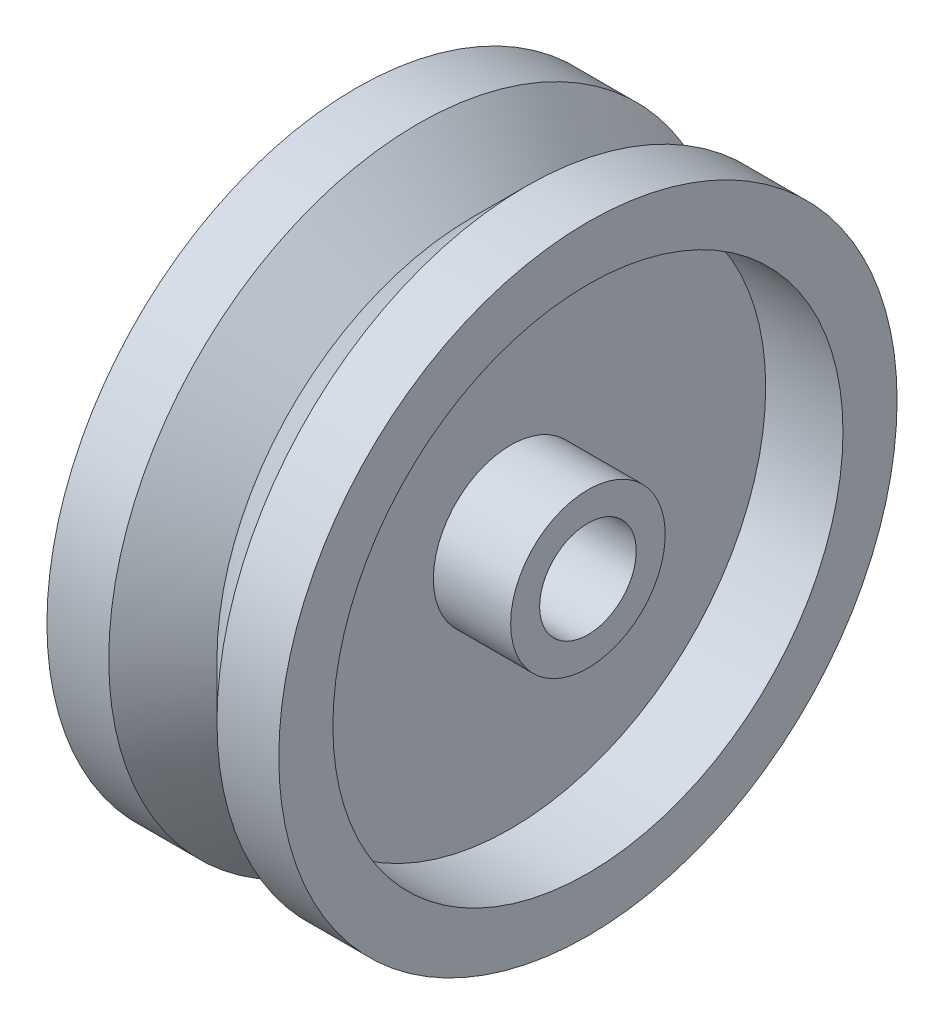
SolidWorks part; units mm, degrees
ref_plane "Front Plane" through (0, 0, 0) normal (0, 0, 1) x (1, 0, 0)
ref_plane "Top Plane" through (0, 0, 0) normal (0, 1, 0) x (1, 0, 0)
ref_plane "Right Plane" through (0, 0, 0) normal (1, 0, 0) x (0, 0, -1)
sketch "Sketch1" plane through (0, 0, 0) normal (0, 1, 0) x (1, 0, 0)
  line L0 (-45.0431, 0) -> (59.0517, 0) construction
  line L1 (0, 38.3621) -> (0, -43.319) construction
  line L2 (-7.5, 3.125) -> (7.5, 3.125)
  line L3 (7.5, 3.125) -> (7.5, 5)
  line L4 (-7.5, 3.125) -> (-7.5, 5)
  line L5 (-7.5, 20) -> (-3.5, 20)
  line L6 (-7.5, 5) -> (-2.5, 5)
  line L7 (-7.5, 16.5) -> (-2.5, 16.5)
  line L8 (-2.5, 16.5) -> (-2.5, 5)
  line L9 (2.5, 16.5) -> (2.5, 5)
  line L10 (2.5, 16.5) -> (7.5, 16.5)
  line L11 (2.5, 5) -> (7.5, 5)
  line L12 (-7.5, 16.5) -> (-7.5, 20)
  line L13 (7.5, 16.5) -> (7.5, 20)
  line L14 (0, 16.5) -> (-3.5, 20)
  line L15 (0, 16.5) -> (3.5, 20)
  line L16 (3.5, 20) -> (7.5, 20)
  point P7 (0, 3.125)
  dimension "D1" = 6.25
  dimension "D2" = 15
  dimension "D3" = 40
  dimension "D4" = 10
  dimension "D5" = 33
  dimension "D6" = 5
  dimension "D7" = 4
revolve "Revolve1" add sketch "Sketch1" angle 360 about L0
